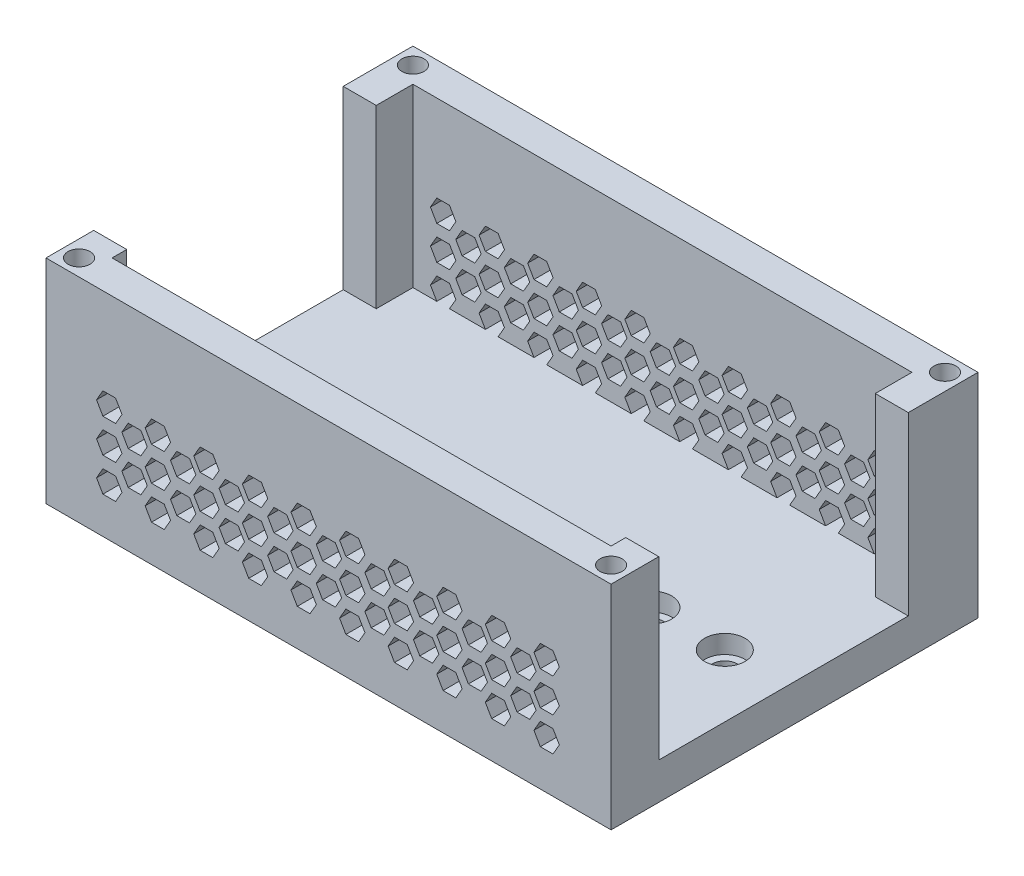
SolidWorks part; units mm, degrees
ref_plane "Front Plane" through (0, 0, 0) normal (0, 0, 1) x (1, 0, 0)
ref_plane "Top Plane" through (0, 0, 0) normal (0, 1, 0) x (1, 0, 0)
ref_plane "Right Plane" through (0, 0, 0) normal (1, 0, 0) x (0, 0, -1)
sketch "Sketch1" plane through (0, 0, 0) normal (0, 1, 0) x (1, 0, 0)
  line L0 (-4.5, 45.5) -> (72.5, 45.5)
  line L1 (0, 0) -> (68, 0)
  line L2 (0, 0) -> (0, 2)
  line L3 (0, 41) -> (68, 41)
  line L4 (68, 0) -> (68, 2)
  line L5 (72.5, -4.5) -> (72.5, 2)
  line L6 (-4.5, -4.5) -> (72.5, -4.5)
  line L7 (-4.5, -4.5) -> (-4.5, 2)
  line L8 (-4.5, 45.5) -> (0, 41) construction
  line L9 (0, 36) -> (-4.5, 36)
  line L10 (34, 20.5) -> (72.9294, 20.5) construction
  line L11 (34, 41) -> (34, 0) construction
  line L12 (0, 2) -> (-4.5, 2)
  line L13 (68, 36) -> (72.5, 36)
  line L14 (68, 2) -> (72.5, 2)
  line L15 (0, 36) -> (0, 41)
  line L16 (0, 0) -> (0, 41) construction
  line L17 (68, 36) -> (68, 41)
  line L18 (68, 0) -> (68, 41) construction
  line L19 (72.5, 36) -> (72.5, 45.5)
  line L20 (72.5, -4.5) -> (72.5, 45.5) construction
  line L21 (-4.5, 36) -> (-4.5, 45.5)
  line L22 (-4.5, -4.5) -> (-4.5, 45.5) construction
  circle A0 centre (-2.25, 43.25) radius 1.5
  circle A4 centre (70.25, 43.25) radius 1.5
  circle A5 centre (70.25, -2.25) radius 1.5
  circle A6 centre (-2.25, -2.25) radius 1.5
  dimension "D7" = 3
  dimension "D1" = 68
  dimension "D2" = 50
  dimension "D6" = 5
  dimension "D3" = 4.5
extrude "Boss-Extrude1" add sketch "Sketch1" along normal blind 24
sketch "Sketch2" plane through (0, 0, 0) normal (0, -1, 0) x (1, 0, 0)
  line L0 (34, 0) -> (34, -41)
  line L1 (-4.5, 4.5) -> (72.5, 4.5)
  line L2 (-4.5, 4.5) -> (-4.5, -45.5)
  line L3 (-4.5, -45.5) -> (72.5, -45.5)
  line L4 (72.5, 4.5) -> (72.5, -45.5)
  line L5 (0, 0) -> (68, 0) construction
  line L6 (0, -41) -> (68, -41) construction
  circle A0 centre (70.25, 2.25) radius 1.5
  circle A2 centre (-2.25, -43.25) radius 1.5
  circle A3 centre (70.25, -43.25) radius 1.5
  circle A4 centre (4, -19.5) radius 1.7
  circle A5 centre (14, -19.5) radius 1.7
  circle A6 centre (24, -19.5) radius 1.7
  circle A7 centre (34, -19.5) radius 1.7
  circle A8 centre (44, -19.5) radius 1.7
  circle A9 centre (54, -19.5) radius 1.7
  circle A10 centre (64, -19.5) radius 1.7
  circle A11 centre (-2.25, 2.25) radius 1.5
  dimension "D1" = 3.4
  dimension "D3" = 10
  dimension "D2" = 7
extrude "Boss-Extrude2" add sketch "Sketch2" along normal blind 5
sketch "Sketch3" plane through (0, 0, 0) normal (0, 1, 0) x (1, 0, 0)
  circle A0 centre (4, 19.5) radius 2.75
  circle A1 centre (14, 19.5) radius 2.75
  circle A2 centre (24, 19.5) radius 2.75
  circle A3 centre (34, 19.5) radius 2.75
  circle A4 centre (44, 19.5) radius 2.75
  circle A5 centre (54, 19.5) radius 2.75
  circle A6 centre (64, 19.5) radius 2.75
  dimension "D1" = 5.5
  dimension "D2" = 7
extrude "Cut-Extrude1" cut sketch "Sketch3" against normal blind 2.5
sketch "Sketch5" plane through (0, 0, -45.5) normal (0, 0, -1) x (-1, 0, 0)
  line L0 (-68, 24) -> (-68, -5) construction
  line L1 (4.5, 24) -> (-72.5, 24) construction
  line L2 (4.5, -5) -> (-72.5, -5) construction
  line L3 (-72.5, -5) -> (-72.5, 24) construction
  line L4 (-68, 0) -> (0, 0) construction
  line L5 (0, 0) -> (0, 24) construction
  line L6 (-58.8138, 4.0022) -> (-59.6798, 5.5022)
  line L7 (-61.9879, 1.5) -> (-62.854, 3)
  line L8 (-62.854, 3) -> (-64.586, 3)
  line L9 (-64.586, 3) -> (-65.4521, 1.5)
  line L10 (-65.4521, 1.5) -> (-64.586, 0)
  line L11 (-64.586, 0) -> (-62.854, 0)
  line L12 (-62.854, 0) -> (-61.9879, 1.5)
  line L13 (-59.6798, 5.5022) -> (-61.4119, 5.5022)
  line L14 (-61.4119, 5.5022) -> (-62.2779, 4.0022)
  line L15 (-62.2779, 4.0022) -> (-61.4119, 2.5022)
  line L16 (-61.4119, 2.5022) -> (-59.6798, 2.5022)
  line L17 (-59.6798, 2.5022) -> (-58.8138, 4.0022)
  line L18 (-52.1915, 4.0022) -> (-53.0575, 5.5022)
  line L19 (-53.0575, 5.5022) -> (-54.7896, 5.5022)
  line L20 (-54.7896, 5.5022) -> (-55.6556, 4.0022)
  line L21 (-55.6556, 4.0022) -> (-54.7896, 2.5022)
  line L22 (-54.7896, 2.5022) -> (-53.0575, 2.5022)
  line L23 (-53.0575, 2.5022) -> (-52.1915, 4.0022)
  line L24 (-55.3656, 1.5) -> (-56.2316, 3)
  line L25 (-56.2316, 3) -> (-57.9637, 3)
  line L26 (-57.9637, 3) -> (-58.8297, 1.5)
  line L27 (-58.8297, 1.5) -> (-57.9637, 0)
  line L28 (-57.9637, 0) -> (-56.2316, 0)
  line L29 (-56.2316, 0) -> (-55.3656, 1.5)
  line L30 (-45.5692, 4.0022) -> (-46.4352, 5.5022)
  line L31 (-46.4352, 5.5022) -> (-48.1672, 5.5022)
  line L32 (-48.1672, 5.5022) -> (-49.0333, 4.0022)
  line L33 (-49.0333, 4.0022) -> (-48.1672, 2.5022)
  line L34 (-48.1672, 2.5022) -> (-46.4352, 2.5022)
  line L35 (-46.4352, 2.5022) -> (-45.5692, 4.0022)
  line L36 (-48.7433, 1.5) -> (-49.6093, 3)
  line L37 (-49.6093, 3) -> (-51.3414, 3)
  line L38 (-51.3414, 3) -> (-52.2074, 1.5)
  line L39 (-52.2074, 1.5) -> (-51.3414, 0)
  line L40 (-51.3414, 0) -> (-49.6093, 0)
  line L41 (-49.6093, 0) -> (-48.7433, 1.5)
  line L42 (-38.9468, 4.0022) -> (-39.8129, 5.5022)
  line L43 (-39.8129, 5.5022) -> (-41.5449, 5.5022)
  line L44 (-41.5449, 5.5022) -> (-42.4109, 4.0022)
  line L45 (-42.4109, 4.0022) -> (-41.5449, 2.5022)
  line L46 (-41.5449, 2.5022) -> (-39.8129, 2.5022)
  line L47 (-39.8129, 2.5022) -> (-38.9468, 4.0022)
  line L48 (-42.121, 1.5) -> (-42.987, 3)
  line L49 (-42.987, 3) -> (-44.719, 3)
  line L50 (-44.719, 3) -> (-45.5851, 1.5)
  line L51 (-45.5851, 1.5) -> (-44.719, 0)
  line L52 (-44.719, 0) -> (-42.987, 0)
  line L53 (-42.987, 0) -> (-42.121, 1.5)
  line L54 (-32.3245, 4.0022) -> (-33.1905, 5.5022)
  line L55 (-33.1905, 5.5022) -> (-34.9226, 5.5022)
  line L56 (-34.9226, 5.5022) -> (-35.7886, 4.0022)
  line L57 (-35.7886, 4.0022) -> (-34.9226, 2.5022)
  line L58 (-34.9226, 2.5022) -> (-33.1905, 2.5022)
  line L59 (-33.1905, 2.5022) -> (-32.3245, 4.0022)
  line L60 (-35.4986, 1.5) -> (-36.3647, 3)
  line L61 (-36.3647, 3) -> (-38.0967, 3)
  line L62 (-38.0967, 3) -> (-38.9627, 1.5)
  line L63 (-38.9627, 1.5) -> (-38.0967, 0)
  line L64 (-38.0967, 0) -> (-36.3647, 0)
  line L65 (-36.3647, 0) -> (-35.4986, 1.5)
  line L66 (-25.7022, 4.0022) -> (-26.5682, 5.5022)
  line L67 (-26.5682, 5.5022) -> (-28.3003, 5.5022)
  line L68 (-28.3003, 5.5022) -> (-29.1663, 4.0022)
  line L69 (-29.1663, 4.0022) -> (-28.3003, 2.5022)
  line L70 (-28.3003, 2.5022) -> (-26.5682, 2.5022)
  line L71 (-26.5682, 2.5022) -> (-25.7022, 4.0022)
  line L72 (-28.8763, 1.5) -> (-29.7423, 3)
  line L73 (-29.7423, 3) -> (-31.4744, 3)
  line L74 (-31.4744, 3) -> (-32.3404, 1.5)
  line L75 (-32.3404, 1.5) -> (-31.4744, 0)
  line L76 (-31.4744, 0) -> (-29.7423, 0)
  line L77 (-29.7423, 0) -> (-28.8763, 1.5)
  line L78 (-19.0799, 4.0022) -> (-19.9459, 5.5022)
  line L79 (-19.9459, 5.5022) -> (-21.6779, 5.5022)
  line L80 (-21.6779, 5.5022) -> (-22.544, 4.0022)
  line L81 (-22.544, 4.0022) -> (-21.6779, 2.5022)
  line L82 (-21.6779, 2.5022) -> (-19.9459, 2.5022)
  line L83 (-19.9459, 2.5022) -> (-19.0799, 4.0022)
  line L84 (-22.254, 1.5) -> (-23.12, 3)
  line L85 (-23.12, 3) -> (-24.8521, 3)
  line L86 (-24.8521, 3) -> (-25.7181, 1.5)
  line L87 (-25.7181, 1.5) -> (-24.8521, 0)
  line L88 (-24.8521, 0) -> (-23.12, 0)
  line L89 (-23.12, 0) -> (-22.254, 1.5)
  line L90 (-12.4575, 4.0022) -> (-13.3236, 5.5022)
  line L91 (-13.3236, 5.5022) -> (-15.0556, 5.5022)
  line L92 (-15.0556, 5.5022) -> (-15.9216, 4.0022)
  line L93 (-15.9216, 4.0022) -> (-15.0556, 2.5022)
  line L94 (-15.0556, 2.5022) -> (-13.3236, 2.5022)
  line L95 (-13.3236, 2.5022) -> (-12.4575, 4.0022)
  line L96 (-15.6317, 1.5) -> (-16.4977, 3)
  line L97 (-16.4977, 3) -> (-18.2297, 3)
  line L98 (-18.2297, 3) -> (-19.0958, 1.5)
  line L99 (-19.0958, 1.5) -> (-18.2297, 0)
  line L100 (-18.2297, 0) -> (-16.4977, 0)
  line L101 (-16.4977, 0) -> (-15.6317, 1.5)
  line L102 (-5.8352, 4.0022) -> (-6.7012, 5.5022)
  line L103 (-6.7012, 5.5022) -> (-8.4333, 5.5022)
  line L104 (-8.4333, 5.5022) -> (-9.2993, 4.0022)
  line L105 (-9.2993, 4.0022) -> (-8.4333, 2.5022)
  line L106 (-8.4333, 2.5022) -> (-6.7012, 2.5022)
  line L107 (-6.7012, 2.5022) -> (-5.8352, 4.0022)
  line L108 (-9.0093, 1.5) -> (-9.8754, 3)
  line L109 (-9.8754, 3) -> (-11.6074, 3)
  line L110 (-11.6074, 3) -> (-12.4734, 1.5)
  line L111 (-12.4734, 1.5) -> (-11.6074, 0)
  line L112 (-11.6074, 0) -> (-9.8754, 0)
  line L113 (-9.8754, 0) -> (-9.0093, 1.5)
  line L120 (-2.387, 1.5) -> (-3.253, 3)
  line L121 (-3.253, 3) -> (-4.9851, 3)
  line L122 (-4.9851, 3) -> (-5.8511, 1.5)
  line L123 (-5.8511, 1.5) -> (-4.9851, 0)
  line L124 (-4.9851, 0) -> (-3.253, 0)
  line L125 (-3.253, 0) -> (-2.387, 1.5)
  line L126 (-58.8138, 8.6022) -> (-59.6798, 10.1022)
  line L127 (-59.6798, 10.1022) -> (-61.4119, 10.1022)
  line L128 (-61.4119, 10.1022) -> (-62.2779, 8.6022)
  line L129 (-62.2779, 8.6022) -> (-61.4119, 7.1022)
  line L130 (-61.4119, 7.1022) -> (-59.6798, 7.1022)
  line L131 (-59.6798, 7.1022) -> (-58.8138, 8.6022)
  line L132 (-61.9879, 6.1) -> (-62.854, 7.6)
  line L133 (-62.854, 7.6) -> (-64.586, 7.6)
  line L134 (-64.586, 7.6) -> (-65.4521, 6.1)
  line L135 (-65.4521, 6.1) -> (-64.586, 4.6)
  line L136 (-64.586, 4.6) -> (-62.854, 4.6)
  line L137 (-62.854, 4.6) -> (-61.9879, 6.1)
  line L138 (-52.1915, 8.6022) -> (-53.0575, 10.1022)
  line L139 (-53.0575, 10.1022) -> (-54.7896, 10.1022)
  line L140 (-54.7896, 10.1022) -> (-55.6556, 8.6022)
  line L141 (-55.6556, 8.6022) -> (-54.7896, 7.1022)
  line L142 (-54.7896, 7.1022) -> (-53.0575, 7.1022)
  line L143 (-53.0575, 7.1022) -> (-52.1915, 8.6022)
  line L144 (-55.3656, 6.1) -> (-56.2316, 7.6)
  line L145 (-56.2316, 7.6) -> (-57.9637, 7.6)
  line L146 (-57.9637, 7.6) -> (-58.8297, 6.1)
  line L147 (-58.8297, 6.1) -> (-57.9637, 4.6)
  line L148 (-57.9637, 4.6) -> (-56.2316, 4.6)
  line L149 (-56.2316, 4.6) -> (-55.3656, 6.1)
  line L150 (-45.5692, 8.6022) -> (-46.4352, 10.1022)
  line L151 (-46.4352, 10.1022) -> (-48.1672, 10.1022)
  line L152 (-48.1672, 10.1022) -> (-49.0333, 8.6022)
  line L153 (-49.0333, 8.6022) -> (-48.1672, 7.1022)
  line L154 (-48.1672, 7.1022) -> (-46.4352, 7.1022)
  line L155 (-46.4352, 7.1022) -> (-45.5692, 8.6022)
  line L156 (-48.7433, 6.1) -> (-49.6093, 7.6)
  line L157 (-49.6093, 7.6) -> (-51.3414, 7.6)
  line L158 (-51.3414, 7.6) -> (-52.2074, 6.1)
  line L159 (-52.2074, 6.1) -> (-51.3414, 4.6)
  line L160 (-51.3414, 4.6) -> (-49.6093, 4.6)
  line L161 (-49.6093, 4.6) -> (-48.7433, 6.1)
  line L162 (-38.9468, 8.6022) -> (-39.8129, 10.1022)
  line L163 (-39.8129, 10.1022) -> (-41.5449, 10.1022)
  line L164 (-41.5449, 10.1022) -> (-42.4109, 8.6022)
  line L165 (-42.4109, 8.6022) -> (-41.5449, 7.1022)
  line L166 (-41.5449, 7.1022) -> (-39.8129, 7.1022)
  line L167 (-39.8129, 7.1022) -> (-38.9468, 8.6022)
  line L168 (-42.121, 6.1) -> (-42.987, 7.6)
  line L169 (-42.987, 7.6) -> (-44.719, 7.6)
  line L170 (-44.719, 7.6) -> (-45.5851, 6.1)
  line L171 (-45.5851, 6.1) -> (-44.719, 4.6)
  line L172 (-44.719, 4.6) -> (-42.987, 4.6)
  line L173 (-42.987, 4.6) -> (-42.121, 6.1)
  line L174 (-32.3245, 8.6022) -> (-33.1905, 10.1022)
  line L175 (-33.1905, 10.1022) -> (-34.9226, 10.1022)
  line L176 (-34.9226, 10.1022) -> (-35.7886, 8.6022)
  line L177 (-35.7886, 8.6022) -> (-34.9226, 7.1022)
  line L178 (-34.9226, 7.1022) -> (-33.1905, 7.1022)
  line L179 (-33.1905, 7.1022) -> (-32.3245, 8.6022)
  line L180 (-35.4986, 6.1) -> (-36.3647, 7.6)
  line L181 (-36.3647, 7.6) -> (-38.0967, 7.6)
  line L182 (-38.0967, 7.6) -> (-38.9627, 6.1)
  line L183 (-38.9627, 6.1) -> (-38.0967, 4.6)
  line L184 (-38.0967, 4.6) -> (-36.3647, 4.6)
  line L185 (-36.3647, 4.6) -> (-35.4986, 6.1)
  line L186 (-25.7022, 8.6022) -> (-26.5682, 10.1022)
  line L187 (-26.5682, 10.1022) -> (-28.3003, 10.1022)
  line L188 (-28.3003, 10.1022) -> (-29.1663, 8.6022)
  line L189 (-29.1663, 8.6022) -> (-28.3003, 7.1022)
  line L190 (-28.3003, 7.1022) -> (-26.5682, 7.1022)
  line L191 (-26.5682, 7.1022) -> (-25.7022, 8.6022)
  line L192 (-28.8763, 6.1) -> (-29.7423, 7.6)
  line L193 (-29.7423, 7.6) -> (-31.4744, 7.6)
  line L194 (-31.4744, 7.6) -> (-32.3404, 6.1)
  line L195 (-32.3404, 6.1) -> (-31.4744, 4.6)
  line L196 (-31.4744, 4.6) -> (-29.7423, 4.6)
  line L197 (-29.7423, 4.6) -> (-28.8763, 6.1)
  line L198 (-19.0799, 8.6022) -> (-19.9459, 10.1022)
  line L199 (-19.9459, 10.1022) -> (-21.6779, 10.1022)
  line L200 (-21.6779, 10.1022) -> (-22.544, 8.6022)
  line L201 (-22.544, 8.6022) -> (-21.6779, 7.1022)
  line L202 (-21.6779, 7.1022) -> (-19.9459, 7.1022)
  line L203 (-19.9459, 7.1022) -> (-19.0799, 8.6022)
  line L204 (-22.254, 6.1) -> (-23.12, 7.6)
  line L205 (-23.12, 7.6) -> (-24.8521, 7.6)
  line L206 (-24.8521, 7.6) -> (-25.7181, 6.1)
  line L207 (-25.7181, 6.1) -> (-24.8521, 4.6)
  line L208 (-24.8521, 4.6) -> (-23.12, 4.6)
  line L209 (-23.12, 4.6) -> (-22.254, 6.1)
  line L210 (-12.4575, 8.6022) -> (-13.3236, 10.1022)
  line L211 (-13.3236, 10.1022) -> (-15.0556, 10.1022)
  line L212 (-15.0556, 10.1022) -> (-15.9216, 8.6022)
  line L213 (-15.9216, 8.6022) -> (-15.0556, 7.1022)
  line L214 (-15.0556, 7.1022) -> (-13.3236, 7.1022)
  line L215 (-13.3236, 7.1022) -> (-12.4575, 8.6022)
  line L216 (-15.6317, 6.1) -> (-16.4977, 7.6)
  line L217 (-16.4977, 7.6) -> (-18.2297, 7.6)
  line L218 (-18.2297, 7.6) -> (-19.0958, 6.1)
  line L219 (-19.0958, 6.1) -> (-18.2297, 4.6)
  line L220 (-18.2297, 4.6) -> (-16.4977, 4.6)
  line L221 (-16.4977, 4.6) -> (-15.6317, 6.1)
  line L222 (-5.8352, 8.6022) -> (-6.7012, 10.1022)
  line L223 (-6.7012, 10.1022) -> (-8.4333, 10.1022)
  line L224 (-8.4333, 10.1022) -> (-9.2993, 8.6022)
  line L225 (-9.2993, 8.6022) -> (-8.4333, 7.1022)
  line L226 (-8.4333, 7.1022) -> (-6.7012, 7.1022)
  line L227 (-6.7012, 7.1022) -> (-5.8352, 8.6022)
  line L228 (-9.0093, 6.1) -> (-9.8754, 7.6)
  line L229 (-9.8754, 7.6) -> (-11.6074, 7.6)
  line L230 (-11.6074, 7.6) -> (-12.4734, 6.1)
  line L231 (-12.4734, 6.1) -> (-11.6074, 4.6)
  line L232 (-11.6074, 4.6) -> (-9.8754, 4.6)
  line L233 (-9.8754, 4.6) -> (-9.0093, 6.1)
  line L240 (-2.387, 6.1) -> (-3.253, 7.6)
  line L241 (-3.253, 7.6) -> (-4.9851, 7.6)
  line L242 (-4.9851, 7.6) -> (-5.8511, 6.1)
  line L243 (-5.8511, 6.1) -> (-4.9851, 4.6)
  line L244 (-4.9851, 4.6) -> (-3.253, 4.6)
  line L245 (-3.253, 4.6) -> (-2.387, 6.1)
  line L252 (-61.9879, 10.7) -> (-62.854, 12.2)
  line L253 (-62.854, 12.2) -> (-64.586, 12.2)
  line L254 (-64.586, 12.2) -> (-65.4521, 10.7)
  line L255 (-65.4521, 10.7) -> (-64.586, 9.2)
  line L256 (-64.586, 9.2) -> (-62.854, 9.2)
  line L257 (-62.854, 9.2) -> (-61.9879, 10.7)
  line L264 (-55.3656, 10.7) -> (-56.2316, 12.2)
  line L265 (-56.2316, 12.2) -> (-57.9637, 12.2)
  line L266 (-57.9637, 12.2) -> (-58.8297, 10.7)
  line L267 (-58.8297, 10.7) -> (-57.9637, 9.2)
  line L268 (-57.9637, 9.2) -> (-56.2316, 9.2)
  line L269 (-56.2316, 9.2) -> (-55.3656, 10.7)
  line L276 (-48.7433, 10.7) -> (-49.6093, 12.2)
  line L277 (-49.6093, 12.2) -> (-51.3414, 12.2)
  line L278 (-51.3414, 12.2) -> (-52.2074, 10.7)
  line L279 (-52.2074, 10.7) -> (-51.3414, 9.2)
  line L280 (-51.3414, 9.2) -> (-49.6093, 9.2)
  line L281 (-49.6093, 9.2) -> (-48.7433, 10.7)
  line L288 (-42.121, 10.7) -> (-42.987, 12.2)
  line L289 (-42.987, 12.2) -> (-44.719, 12.2)
  line L290 (-44.719, 12.2) -> (-45.5851, 10.7)
  line L291 (-45.5851, 10.7) -> (-44.719, 9.2)
  line L292 (-44.719, 9.2) -> (-42.987, 9.2)
  line L293 (-42.987, 9.2) -> (-42.121, 10.7)
  line L300 (-35.4986, 10.7) -> (-36.3647, 12.2)
  line L301 (-36.3647, 12.2) -> (-38.0967, 12.2)
  line L302 (-38.0967, 12.2) -> (-38.9627, 10.7)
  line L303 (-38.9627, 10.7) -> (-38.0967, 9.2)
  line L304 (-38.0967, 9.2) -> (-36.3647, 9.2)
  line L305 (-36.3647, 9.2) -> (-35.4986, 10.7)
  line L312 (-28.8763, 10.7) -> (-29.7423, 12.2)
  line L313 (-29.7423, 12.2) -> (-31.4744, 12.2)
  line L314 (-31.4744, 12.2) -> (-32.3404, 10.7)
  line L315 (-32.3404, 10.7) -> (-31.4744, 9.2)
  line L316 (-31.4744, 9.2) -> (-29.7423, 9.2)
  line L317 (-29.7423, 9.2) -> (-28.8763, 10.7)
  line L324 (-22.254, 10.7) -> (-23.12, 12.2)
  line L325 (-23.12, 12.2) -> (-24.8521, 12.2)
  line L326 (-24.8521, 12.2) -> (-25.7181, 10.7)
  line L327 (-25.7181, 10.7) -> (-24.8521, 9.2)
  line L328 (-24.8521, 9.2) -> (-23.12, 9.2)
  line L329 (-23.12, 9.2) -> (-22.254, 10.7)
  line L336 (-15.6317, 10.7) -> (-16.4977, 12.2)
  line L337 (-16.4977, 12.2) -> (-18.2297, 12.2)
  line L338 (-18.2297, 12.2) -> (-19.0958, 10.7)
  line L339 (-19.0958, 10.7) -> (-18.2297, 9.2)
  line L340 (-18.2297, 9.2) -> (-16.4977, 9.2)
  line L341 (-16.4977, 9.2) -> (-15.6317, 10.7)
  line L348 (-9.0093, 10.7) -> (-9.8754, 12.2)
  line L349 (-9.8754, 12.2) -> (-11.6074, 12.2)
  line L350 (-11.6074, 12.2) -> (-12.4734, 10.7)
  line L351 (-12.4734, 10.7) -> (-11.6074, 9.2)
  line L352 (-11.6074, 9.2) -> (-9.8754, 9.2)
  line L353 (-9.8754, 9.2) -> (-9.0093, 10.7)
  line L360 (-2.387, 10.7) -> (-3.253, 12.2)
  line L361 (-3.253, 12.2) -> (-4.9851, 12.2)
  line L362 (-4.9851, 12.2) -> (-5.8511, 10.7)
  line L363 (-5.8511, 10.7) -> (-4.9851, 9.2)
  line L364 (-4.9851, 9.2) -> (-3.253, 9.2)
  line L365 (-3.253, 9.2) -> (-2.387, 10.7)
  line L366 (0.7871, 4.0022) -> (-0.0789, 5.5022) [skipped]
  line L367 (-0.0789, 5.5022) -> (-1.8109, 5.5022) [skipped]
  line L368 (-1.8109, 5.5022) -> (-2.677, 4.0022) [skipped]
  line L369 (-2.677, 4.0022) -> (-1.8109, 2.5022) [skipped]
  line L370 (-1.8109, 2.5022) -> (-0.0789, 2.5022) [skipped]
  line L371 (-0.0789, 2.5022) -> (0.7871, 4.0022) [skipped]
  line L372 (0.7871, 8.6022) -> (-0.0789, 10.1022) [skipped]
  line L373 (-0.0789, 10.1022) -> (-1.8109, 10.1022) [skipped]
  line L374 (-1.8109, 10.1022) -> (-2.677, 8.6022) [skipped]
  line L375 (-2.677, 8.6022) -> (-1.8109, 7.1022) [skipped]
  line L376 (-1.8109, 7.1022) -> (-0.0789, 7.1022) [skipped]
  line L377 (-0.0789, 7.1022) -> (0.7871, 8.6022) [skipped]
  line L378 (0.7871, 13.2022) -> (-0.0789, 14.7022) [skipped]
  line L379 (-0.0789, 14.7022) -> (-1.8109, 14.7022) [skipped]
  line L380 (-1.8109, 14.7022) -> (-2.677, 13.2022) [skipped]
  line L381 (-2.677, 13.2022) -> (-1.8109, 11.7022) [skipped]
  line L382 (-1.8109, 11.7022) -> (-0.0789, 11.7022) [skipped]
  line L383 (-0.0789, 11.7022) -> (0.7871, 13.2022) [skipped]
  line L384 (-58.8138, 13.2022) -> (-59.6798, 14.7022) [skipped]
  line L385 (-59.6798, 14.7022) -> (-61.4119, 14.7022) [skipped]
  line L386 (-61.4119, 14.7022) -> (-62.2779, 13.2022) [skipped]
  line L387 (-62.2779, 13.2022) -> (-61.4119, 11.7022) [skipped]
  line L388 (-61.4119, 11.7022) -> (-59.6798, 11.7022) [skipped]
  line L389 (-59.6798, 11.7022) -> (-58.8138, 13.2022) [skipped]
  line L390 (-52.1915, 13.2022) -> (-53.0575, 14.7022) [skipped]
  line L391 (-53.0575, 14.7022) -> (-54.7896, 14.7022) [skipped]
  line L392 (-54.7896, 14.7022) -> (-55.6556, 13.2022) [skipped]
  line L393 (-55.6556, 13.2022) -> (-54.7896, 11.7022) [skipped]
  line L394 (-54.7896, 11.7022) -> (-53.0575, 11.7022) [skipped]
  line L395 (-53.0575, 11.7022) -> (-52.1915, 13.2022) [skipped]
  line L396 (-45.5692, 13.2022) -> (-46.4352, 14.7022) [skipped]
  line L397 (-46.4352, 14.7022) -> (-48.1672, 14.7022) [skipped]
  line L398 (-48.1672, 14.7022) -> (-49.0333, 13.2022) [skipped]
  line L399 (-49.0333, 13.2022) -> (-48.1672, 11.7022) [skipped]
  line L400 (-48.1672, 11.7022) -> (-46.4352, 11.7022) [skipped]
  line L401 (-46.4352, 11.7022) -> (-45.5692, 13.2022) [skipped]
  line L402 (-38.9468, 13.2022) -> (-39.8129, 14.7022) [skipped]
  line L403 (-39.8129, 14.7022) -> (-41.5449, 14.7022) [skipped]
  line L404 (-41.5449, 14.7022) -> (-42.4109, 13.2022) [skipped]
  line L405 (-42.4109, 13.2022) -> (-41.5449, 11.7022) [skipped]
  line L406 (-41.5449, 11.7022) -> (-39.8129, 11.7022) [skipped]
  line L407 (-39.8129, 11.7022) -> (-38.9468, 13.2022) [skipped]
  line L408 (-32.3245, 13.2022) -> (-33.1905, 14.7022) [skipped]
  line L409 (-33.1905, 14.7022) -> (-34.9226, 14.7022) [skipped]
  line L410 (-34.9226, 14.7022) -> (-35.7886, 13.2022) [skipped]
  line L411 (-35.7886, 13.2022) -> (-34.9226, 11.7022) [skipped]
  line L412 (-34.9226, 11.7022) -> (-33.1905, 11.7022) [skipped]
  line L413 (-33.1905, 11.7022) -> (-32.3245, 13.2022) [skipped]
  line L414 (-25.7022, 13.2022) -> (-26.5682, 14.7022) [skipped]
  line L415 (-26.5682, 14.7022) -> (-28.3003, 14.7022) [skipped]
  line L416 (-28.3003, 14.7022) -> (-29.1663, 13.2022) [skipped]
  line L417 (-29.1663, 13.2022) -> (-28.3003, 11.7022) [skipped]
  line L418 (-28.3003, 11.7022) -> (-26.5682, 11.7022) [skipped]
  line L419 (-26.5682, 11.7022) -> (-25.7022, 13.2022) [skipped]
  line L420 (-19.0799, 13.2022) -> (-19.9459, 14.7022) [skipped]
  line L421 (-19.9459, 14.7022) -> (-21.6779, 14.7022) [skipped]
  line L422 (-21.6779, 14.7022) -> (-22.544, 13.2022) [skipped]
  line L423 (-22.544, 13.2022) -> (-21.6779, 11.7022) [skipped]
  line L424 (-21.6779, 11.7022) -> (-19.9459, 11.7022) [skipped]
  line L425 (-19.9459, 11.7022) -> (-19.0799, 13.2022) [skipped]
  line L426 (-12.4575, 13.2022) -> (-13.3236, 14.7022) [skipped]
  line L427 (-13.3236, 14.7022) -> (-15.0556, 14.7022) [skipped]
  line L428 (-15.0556, 14.7022) -> (-15.9216, 13.2022) [skipped]
  line L429 (-15.9216, 13.2022) -> (-15.0556, 11.7022) [skipped]
  line L430 (-15.0556, 11.7022) -> (-13.3236, 11.7022) [skipped]
  line L431 (-13.3236, 11.7022) -> (-12.4575, 13.2022) [skipped]
  line L432 (-5.8352, 13.2022) -> (-6.7012, 14.7022) [skipped]
  line L433 (-6.7012, 14.7022) -> (-8.4333, 14.7022) [skipped]
  line L434 (-8.4333, 14.7022) -> (-9.2993, 13.2022) [skipped]
  line L435 (-9.2993, 13.2022) -> (-8.4333, 11.7022) [skipped]
  line L436 (-8.4333, 11.7022) -> (-6.7012, 11.7022) [skipped]
  line L437 (-6.7012, 11.7022) -> (-5.8352, 13.2022) [skipped]
  circle A0 centre (-63.72, 1.5) radius 1.5 construction
  dimension "D2" = 3
  dimension "D1" = 4.5
  dimension "D3" = 1.5
  dimension "D4" = 4.28
  dimension "D5" = 10
  dimension "1" = 1
  dimension "D6" = 3
extrude "Cut-Extrude2" cut sketch "Sketch5" against normal through all
